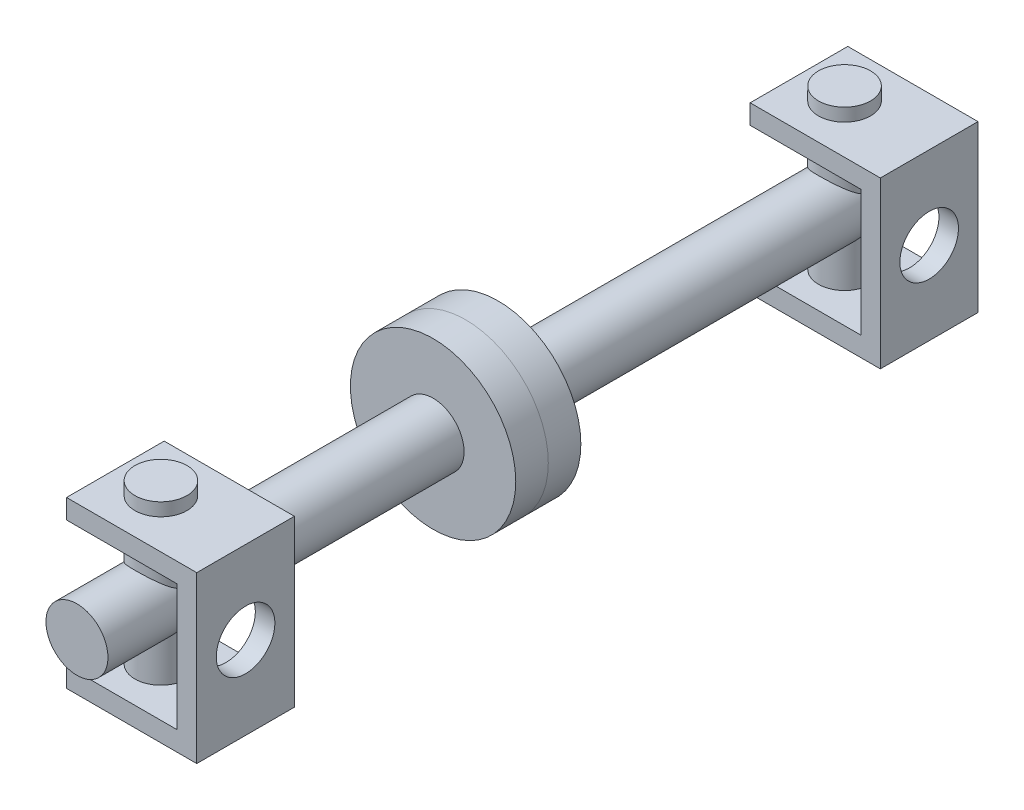
SolidWorks part; units mm, degrees
ref_plane "Front Plane" through (0, 0, 0) normal (0, 0, 1) x (1, 0, 0)
ref_plane "Top Plane" through (0, 0, 0) normal (0, 1, 0) x (1, 0, 0)
ref_plane "Right Plane" through (0, 0, 0) normal (1, 0, 0) x (0, 0, -1)
sketch "Sketch1" plane through (0, 0, 0) normal (0, 0, 1) x (1, 0, 0)
  line L0 (0, 0) -> (0, -25.4)
  line L1 (0, 0) -> (-20, 0)
  line L2 (0, -25.4) -> (-20, -25.4)
  line L3 (-3, -22.4) -> (-20, -22.4)
  line L4 (-3, -3) -> (-3, -22.4)
  line L5 (-3, -3) -> (-20, -3)
  line L6 (-20, 0) -> (-20, -3)
  line L7 (-20, -22.4) -> (-20, -25.4)
  dimension "D1" = 3
extrude "Boss-Extrude1" add sketch "Sketch1" along normal blind 15
sketch "Sketch2" plane through (0, 0, 0) normal (1, 0, 0) x (0, 0, -1)
  circle A0 centre (-7.5, -12.7) radius 4.5
extrude "Cut-Extrude1" cut sketch "Sketch2" against normal blind 15
sketch "Sketch3" plane through (0, -25.4, 0) normal (0, -1, 0) x (1, 0, 0)
  circle A0 centre (-13, 7.5) radius 4
extrude "Cut-Extrude2" cut sketch "Sketch3" against normal through all
sketch "Sketch4" plane through (0, 0, 0) normal (0, 1, 0) x (1, 0, 0)
  circle A0 centre (-13, -7.5) radius 4
extrude "Boss-Extrude2" add sketch "Sketch4" against normal blind 27 and the other way blind 2
sketch "Sketch5" plane through (0, 0, 15) normal (0, 0, 1) x (1, 0, 0)
  circle A0 centre (-13, -12.7) radius 2.5
extrude "Cut-Extrude3" cut sketch "Sketch5" against normal blind 27
sketch "Sketch6" plane through (0, 0, 15) normal (0, 0, 1) x (1, 0, 0)
  circle A0 centre (-13, -12.7) radius 4.7625
extrude "Boss-Extrude3" add sketch "Sketch6" along normal blind 45.7 and the other way blind 14
sketch "Sketch7" plane through (0, 0, 0) normal (1, 0, 0) x (0, 0, -1)
  line L0 (-105, 0) -> (-105, -25.4)
  line L4 (-105, 0) -> (-120, 0)
  line L5 (-105, -25.4) -> (-120, -25.4)
  line L6 (-120, 0) -> (-120, -25.4)
extrude "Boss-Extrude4" add sketch "Sketch7" against normal blind 20
sketch "Sketch8" plane through (0, 0, 120) normal (0, 0, 1) x (1, 0, 0)
  line L0 (-20, -3) -> (-3, -3)
  line L1 (-20, 0) -> (-20, -25.4) construction
  line L5 (-3, -22.4) -> (-20, -22.4)
  line L6 (-20, -3) -> (-3, -3)
  line L9 (-3, -3) -> (-3, -22.4)
  line L12 (-20, -22.4) -> (-3, -22.4)
sketch "Sketch10" plane through (0, -25.4, 0) normal (0, -1, 0) x (-1, 0, 0)
  circle A0 centre (13, -112.5) radius 4
sketch "Sketch13" plane through (0, 0, 60.7) normal (0, 0, 1) x (1, 0, 0)
  circle A0 centre (-13, -12.7) radius 12.7
extrude "Boss-Extrude7" add sketch "Sketch13" along normal blind 5
sketch "Sketch16" plane through (0, 0, 65.7) normal (0, 0, 1) x (1, 0, 0)
  circle A0 centre (-13, -12.7) radius 12.7
extrude "Boss-Extrude8" add sketch "Sketch16" along normal blind 5 separate body
sketch "Sketch17" plane through (0, 0, 70.7) normal (0, 0, 1) x (1, 0, 0)
  circle A0 centre (-13, -12.7) radius 2.5
  dimension "D1" = 5
extrude "Cut-Extrude6" cut sketch "Sketch17" along normal blind 54.7
sketch "Sketch18" plane through (0, 0, 70.7) normal (0, 0, 1) x (1, 0, 0)
  circle A0 centre (-13, -12.7) radius 4.7625
extrude "Boss-Extrude9" add sketch "Sketch18" along normal blind 54.7
sketch "Sketch19" plane through (0, 0, 120) normal (0, 0, 1) x (1, 0, 0)
  line L0 (-20, -3) -> (-3, -3)
  line L1 (-3, -3) -> (-3, -22.4)
  line L2 (-3, -22.4) -> (-20, -22.4)
  circle M1 centre (-13, -12.7) radius 4.7625
  line M4 (-20, 0) -> (-20, -25.4)
extrude "Cut-Extrude7" cut sketch "Sketch19" against normal blind 20 and the other way through all contours L2 L1 L0 M4 M1
extrude "Cut-Extrude8" cut sketch "Sketch10" against normal through all contours A0
sketch "Sketch20" plane through (0, -25.4, 0) normal (0, -1, 0) x (1, 0, 0)
  circle A0 centre (-13, 112.5) radius 4
extrude "Boss-Extrude10" add sketch "Sketch20" along normal blind 2 and the other way blind 27.4
sketch "Sketch21" plane through (0, 0, 0) normal (1, 0, 0) x (0, 0, -1)
  circle A0 centre (-112.5, -12.7) radius 4.5
  dimension "D1" = 9
extrude "Cut-Extrude9" cut sketch "Sketch21" against normal blind 8
